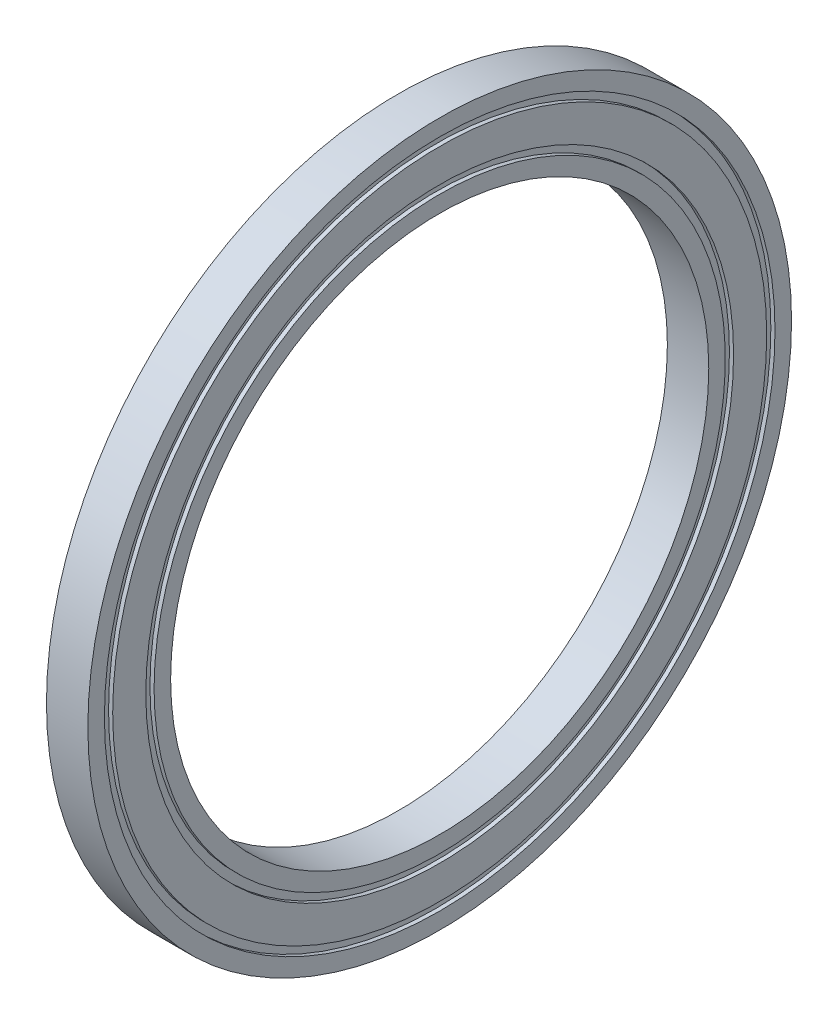
SolidWorks part; units mm, degrees
ref_plane "Front Plane" through (0, 0, 0) normal (0, 0, 1) x (1, 0, 0)
ref_plane "Top Plane" through (0, 0, 0) normal (0, 1, 0) x (1, 0, 0)
ref_plane "Right Plane" through (0, 0, 0) normal (1, 0, 0) x (0, 0, -1)
sketch "Sketch1" plane through (0, 0, 0) normal (0, 0, 1) x (1, 0, 0)
  line L0 (0, 0) -> (0, 32.5) construction
  line L1 (0, 32.5) -> (0, 42.5) construction
  line L2 (-2.5, 42.5) -> (2.5, 42.5)
  line L3 (2.5, 42.5) -> (2.5, 40.5)
  line L4 (2.5, 40.5) -> (2, 40.5)
  line L5 (2, 40.5) -> (2, 39.5)
  line L6 (2, 39.5) -> (2.5, 39.5)
  line L7 (2.5, 39.5) -> (2.5, 35.5)
  line L8 (2.5, 37.5) -> (0, 37.5) construction
  line L9 (2, 35.5) -> (2.5, 35.5)
  line L10 (2, 34.5) -> (2, 35.5)
  line L11 (2.5, 34.5) -> (2, 34.5)
  line L12 (2.5, 32.5) -> (2.5, 34.5)
  line L13 (-2.5, 32.5) -> (2.5, 32.5)
  line L14 (-2.5, 32.5) -> (-2.5, 34.5)
  line L15 (-2.5, 34.5) -> (-2, 34.5)
  line L16 (-2, 34.5) -> (-2, 35.5)
  line L17 (-2, 35.5) -> (-2.5, 35.5)
  line L18 (-2.5, 39.5) -> (-2.5, 35.5)
  line L19 (-2, 39.5) -> (-2.5, 39.5)
  line L20 (-2, 40.5) -> (-2, 39.5)
  line L21 (-2.5, 40.5) -> (-2, 40.5)
  line L22 (-2.5, 42.5) -> (-2.5, 40.5)
  line L23 (0, 0) -> (13.2088, 0) construction
  dimension "D1" = 5
  dimension "D2" = 2
  dimension "D3" = 0.5
  dimension "D4" = 5
  dimension "D5" = 2
  dimension "D6" = 2
  dimension "D7" = 37.5
revolve "Revolve1" add sketch "Sketch1" angle 360 about L23
